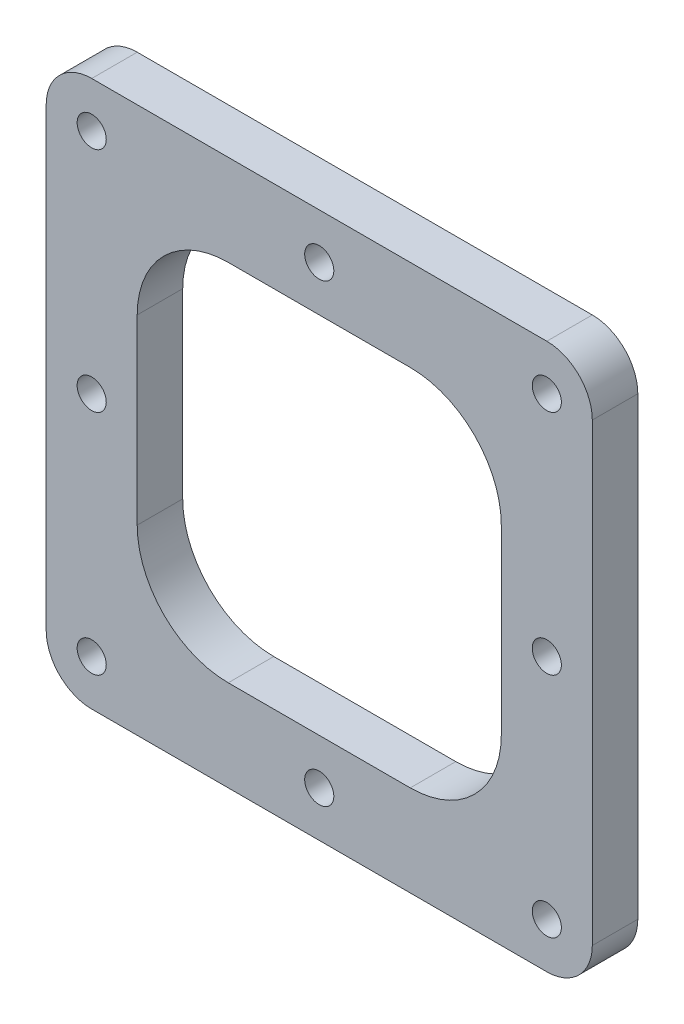
SolidWorks part; units mm, degrees
ref_plane "前视基准面" through (0, 0, 0) normal (0, 0, 1) x (1, 0, 0)
ref_plane "上视基准面" through (0, 0, 0) normal (0, 1, 0) x (1, 0, 0)
ref_plane "右视基准面" through (0, 0, 0) normal (1, 0, 0) x (0, 0, -1)
other "Configuration Table"
sketch "草图1" plane through (0, 0, 0) normal (0, 0, 1) x (1, 0, 0)
  line L1 (5, 0) -> (55, 0)
  line L2 (0, 5) -> (0, 55)
  line L3 (5, 60) -> (55, 60)
  line L4 (60, 5) -> (60, 55)
  arc A0 (5, 0) -> (0, 5) centre (5, 5) cw
  arc A1 (55, 0) -> (60, 5) centre (55, 5) ccw
  arc A2 (55, 60) -> (60, 55) centre (55, 55) cw
  arc A3 (0, 55) -> (5, 60) centre (5, 55) cw
  point P7 (0, 0)
  point P10 (60, 0)
  point P13 (60, 60)
  dimension "D3" = 5
  dimension "D1" = 60
  dimension "D2" = 60
extrude "凸台-拉伸1" add sketch "草图1" along normal blind 5
sketch "草图2" plane through (0, 0, 5) normal (0, 0, 1) x (1, 0, 0)
  line L6 (5, 55) -> (30, 55) construction
  line L7 (5, 55) -> (5, 30) construction
  line L8 (10, 10) -> (50, 10)
  line L9 (50, 10) -> (50, 50)
  line L10 (50, 50) -> (10, 50)
  line L11 (10, 50) -> (10, 10)
  line L12 (10, 10) -> (50, 10)
  line L13 (50, 10) -> (50, 50)
  line L14 (50, 50) -> (10, 50)
  line L15 (10, 50) -> (10, 10)
  circle A4 centre (5, 55) radius 1.6
  circle A5 centre (30, 55) radius 1.6
  circle A6 centre (55, 55) radius 1.6
  circle A8 centre (55, 30) radius 1.6
  circle A9 centre (30, 5) radius 1.6
  circle A10 centre (55, 5) radius 1.6
  circle A11 centre (5, 30) radius 1.6
  circle A12 centre (5, 5) radius 1.6
  circle A13 centre (30, 30) radius 1.6 [skipped]
  dimension "D2" = 3.2
  dimension "D5" = 25
  dimension "D6" = 25
  dimension "D1" = 10
  dimension "D3" = 3
  dimension "D4" = 3
extrude "切除-拉伸1" cut sketch "草图2" against normal through all
fillet "圆角1" radius 10 4 edges at (10, 10, 2.5) (50, 10, 2.5) (50, 50, 2.5) (10, 50, 2.5)
